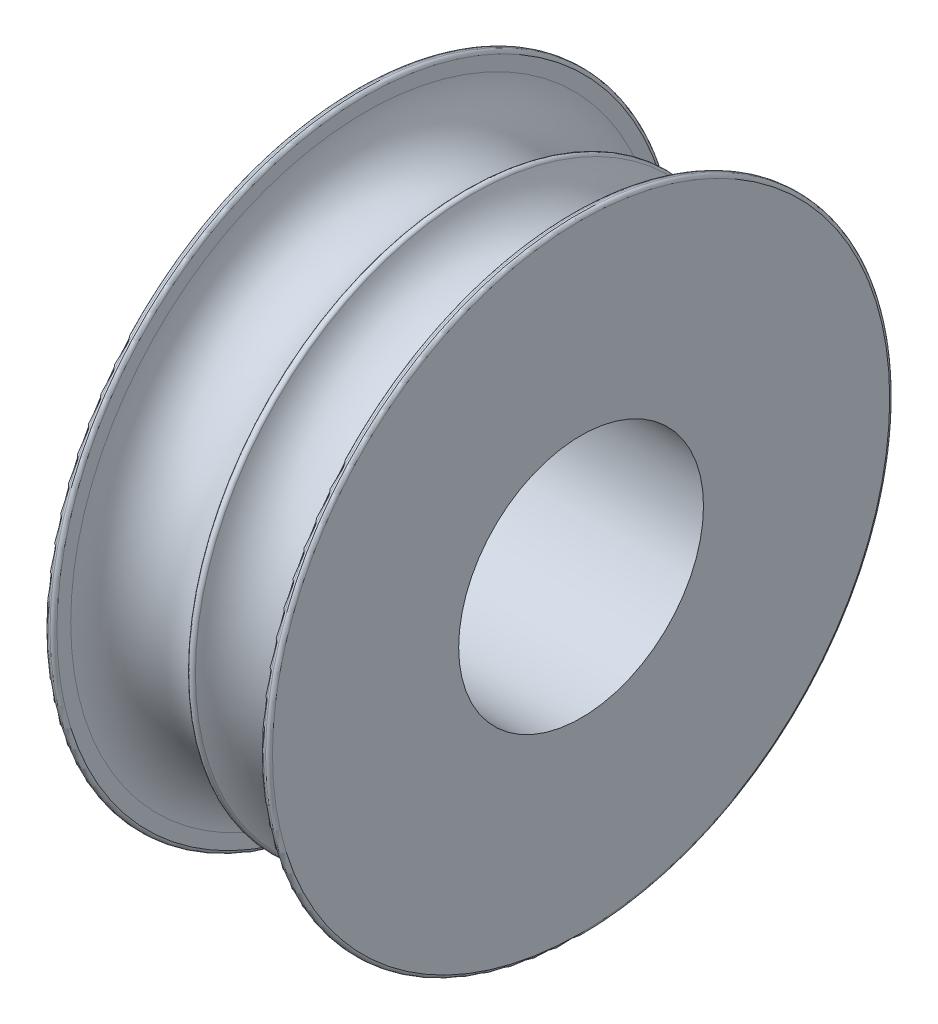
SolidWorks part; units mm, degrees
ref_plane "Front Plane" through (0, 0, 0) normal (0, 0, 1) x (1, 0, 0)
ref_plane "Top Plane" through (0, 0, 0) normal (0, 1, 0) x (1, 0, 0)
ref_plane "Right Plane" through (0, 0, 0) normal (1, 0, 0) x (0, 0, -1)
sketch "Sketch1" plane through (0, 0, 0) normal (0, 1, 0) x (1, 0, 0)
  line L0 (-13, 0) -> (0, 0)
  line L4 (0, 0) -> (0, 18.1)
  line L5 (0, 18.1) -> (-0.5, 18.1)
  line L6 (-0.5, 18.1) -> (-0.5, 17.1)
  line L7 (-6.5, 17.1) -> (-6.5, 0) construction
  line L8 (-12.5, 18.1) -> (-12.5, 17.1)
  line L9 (-13, 18.1) -> (-12.5, 18.1)
  line L10 (-13, 0) -> (-13, 18.1)
  arc A2 (-6.5, 17.1) -> (-0.5, 17.1) centre (-3.5, 17.1) ccw
  arc A3 (-6.5, 17.1) -> (-12.5, 17.1) centre (-9.5, 17.1) cw
  arc A4 (-0.5, 17.1) -> (-6.5, 17.1) centre (-3.5, 17.1) ccw construction
  point P9 (-3.5, 20.1)
  point P17 (-9.5, 20.1)
  dimension "D1" = 6
  dimension "D2" = 20.1
  dimension "D3" = 13
  dimension "D4" = 1
revolve "Revolve1" add sketch "Sketch1" angle 360 about L0
sketch "Sketch2" plane through (0, 0, 0) normal (1, 0, 0) x (0, 0, -1)
  circle A0 centre (0, 0) radius 7.1
  dimension "D1" = 14.2
extrude "Cut-Extrude1" cut sketch "Sketch2" against normal through all both and the other way through all contours A0
fillet "Fillet1" radius 0.2 5 edges at (-6.5, 0, 17.1) (0, 0, 18.1) (-0.5, 0, 18.1) (-12.5, 0, 18.1) (-13, 0, 18.1)
